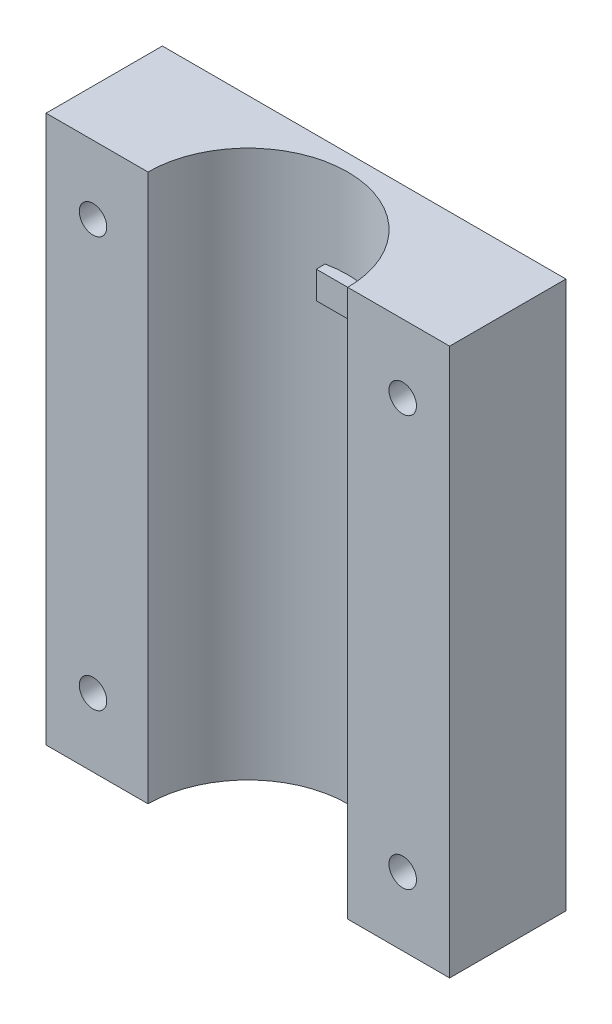
SolidWorks part; units mm, degrees
ref_plane "Front Plane" through (0, 0, 0) normal (0, 0, 1) x (1, 0, 0)
ref_plane "Top Plane" through (0, 0, 0) normal (0, 1, 0) x (1, 0, 0)
ref_plane "Right Plane" through (0, 0, 0) normal (1, 0, 0) x (0, 0, -1)
sketch "Sketch1" plane through (0, 0, 0) normal (0, 0, 1) x (1, 0, 0)
  line L6 (-37.465, -50.8) -> (37.465, -50.8)
  line L7 (-37.465, -50.8) -> (-37.465, 50.8)
  line L8 (-37.465, 50.8) -> (37.465, 50.8)
  line L9 (37.465, -50.8) -> (37.465, 50.8)
  line L10 (-37.465, -50.8) -> (37.465, 50.8) construction
  line L11 (-37.465, 50.8) -> (37.465, -50.8) construction
  point P0 (0, 0)
  dimension "D1" = 74.93
  dimension "D2" = 101.6
extrude "Boss-Extrude2" add sketch "Sketch1" against normal blind 21.59
sketch "Sketch2" plane through (0, 50.8, 0) normal (0, 1, 0) x (1, 0, 0)
  line L0 (37.465, 0) -> (-37.465, 0) construction
  arc A0 (-18.542, 0) -> (18.542, 0) centre (0, 0) cw
  point P7 (0, 18.542)
  dimension "D1" = 18.542
extrude "Cut-Extrude2" cut sketch "Sketch2" against normal through all and the other way through all flip side to cut
ref_plane "Plane1" through (0, 31.75, 0) normal (0, 1, 0) x (1, 0, 0)
sketch "Sketch4" plane through (0, 31.75, 0) normal (0, 1, 0) x (1, 0, 0)
  line L0 (3.81, 16.51) -> (3.81, 21.59)
  line L1 (37.465, 21.59) -> (-37.465, 21.59) construction
  line L2 (3.81, 21.59) -> (-3.81, 21.59)
  line L3 (-3.81, 21.59) -> (-3.81, 16.51)
  line L4 (-3.81, 16.51) -> (3.81, 16.51)
  arc A2 (18.542, 0) -> (-18.542, 0) centre (0, 0) ccw construction
  point P3 (0, 21.59)
  point P5 (0, 18.542)
  dimension "D2" = 2.032
  dimension "D1" = 7.62
extrude "Boss-Extrude3" add sketch "Sketch4" along normal mid plane 5.08
hole_wizard "Tap Drill for 1/4-20 Tap1" positions "Sketch6" profile "Sketch7" hole size "1/4-20" standard "ANSI Inch" end condition through all
sketch "Sketch6" plane through (0, 0, 0) normal (0, 0, 1) x (1, 0, 0)
  line L0 (-37.465, 50.8) -> (-37.465, -50.8) construction
  line L3 (-18.542, 50.8) -> (-37.465, 50.8) construction
  line L4 (37.465, -50.8) -> (37.465, 50.8) construction
  line L7 (-37.465, -50.8) -> (-18.542, -50.8) construction
  point P0 (-28.7528, 38.1)
  point P2 (28.7528, 38.1)
  point P4 (-28.7528, -38.1)
  point P6 (28.7528, -38.1)
  point P33 (0, 0)
  dimension "D1" = 8.7122
  dimension "D2" = 12.7
  dimension "D3" = 8.7122
  dimension "D4" = 12.7
sketch "Sketch7" plane through (-28.7528, 38.1, 0) normal (1, 0, 0) x (0, -1, 0)
  line L0 (0, 0) -> (0, 21.59)
  line L1 (0, 21.59) -> (2.5527, 21.59)
  line L2 (2.5527, 21.59) -> (2.5527, 0)
  line L5 (2.5527, 0) -> (0, 0)
  line L11 (0, -6.35) -> (0, 107.95) construction
  dimension "Thru Hole Dia." = 5.1054
  dimension "Thru Hole Depth" = 21.59
